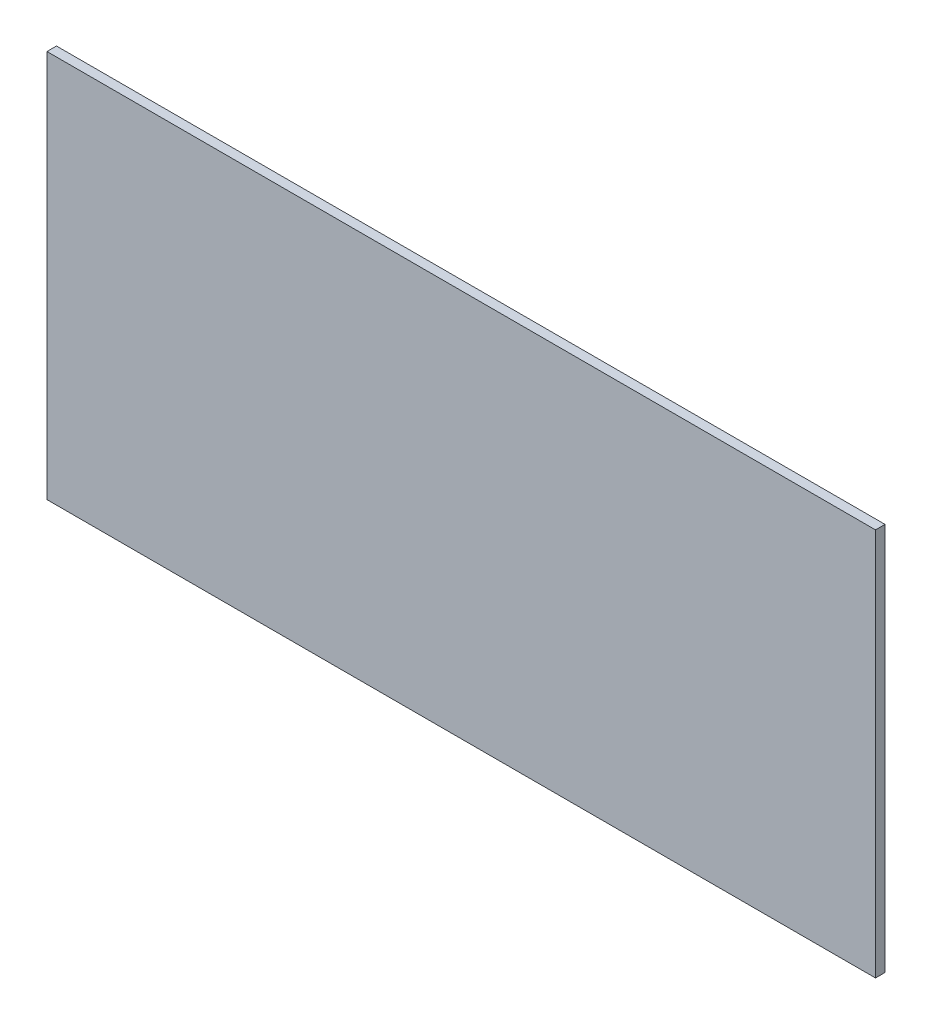
SolidWorks part; units mm, degrees
ref_plane "Plan de face" through (0, 0, 0) normal (0, 0, 1) x (1, 0, 0)
ref_plane "Plan de dessus" through (0, 0, 0) normal (0, 1, 0) x (1, 0, 0)
ref_plane "Plan de droite" through (0, 0, 0) normal (1, 0, 0) x (0, 0, -1)
sketch "Esquisse1" plane through (0, 0, 0) normal (0, 0, 1) x (1, 0, 0)
  line L1 (-174, -81.5) -> (174, -81.5)
  line L2 (-174, -81.5) -> (-174, 81.5)
  line L3 (-174, 81.5) -> (174, 81.5)
  line L4 (174, -81.5) -> (174, 81.5)
  line L5 (-174, -81.5) -> (174, 81.5) construction
  line L6 (-174, 81.5) -> (174, -81.5) construction
  point P0 (0, 0)
  dimension "D1" = 348
  dimension "D2" = 163
extrude "Boss.-Extru.1" add sketch "Esquisse1" along normal blind 4
